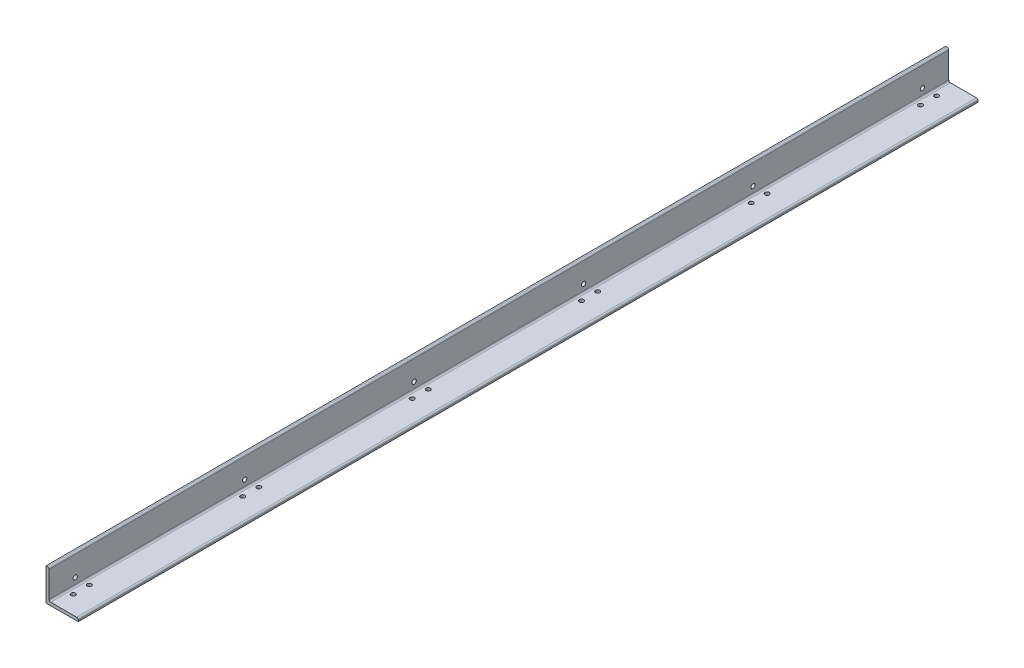
SolidWorks part; units mm, degrees
material "6061 Alloy"
ref_plane "Front Plane" through (0, 0, 0) normal (0, 0, 1) x (1, 0, 0)
ref_plane "Top Plane" through (0, 0, 0) normal (0, 1, 0) x (1, 0, 0)
ref_plane "Right Plane" through (0, 0, 0) normal (1, 0, 0) x (0, 0, -1)
sketch "Sketch1" plane through (0, 0, 0) normal (0, 0, 1) x (1, 0, 0)
  line L0 (0, 0) -> (0, 50.8)
  line L1 (0, 50.8) -> (4.7625, 50.8)
  line L2 (4.7625, 50.8) -> (4.7625, 4.7625)
  line L3 (4.7625, 4.7625) -> (50.8, 4.7625)
  line L4 (50.8, 4.7625) -> (50.8, 0)
  line L5 (50.8, 0) -> (0, 0)
  dimension "D1" = 50.8
  dimension "D2" = 50.8
  dimension "D3" = 4.7625
extrude "Boss-Extrude1" add sketch "Sketch1" along normal mid plane 1416.05
fillet "Fillet1" radius 2.54 3 edges at (50.8, 4.7625, 0) (4.7625, 4.7625, 0) (4.7625, 50.8, 0)
hole_wizard "1/4 Clearance Hole1" positions "Sketch9" profile "Sketch8" hole size "1/4" standard "ANSI Inch" end condition up to next
sketch "Sketch9" plane through (0, 4.7625, 0) normal (0, 1, 0) x (1, 0, 0)
  line L2 (48.26, -708.025) -> (7.3025, -708.025) construction
  line L3 (50.8, 708.025) -> (50.8, -708.025) construction
  point P1 (14.2875, -679.45)
  point P13 (14.2875, -654.05)
  dimension "D1" = 36.5125
  dimension "D2" = 28.575
  dimension "D3" = 25.4
sketch "Sketch8" plane through (14.2875, 4.7625, 679.45) normal (1, 0, 0) x (0, 0, 1)
  line L0 (0, 0) -> (0, 4.7625)
  line L1 (0, 4.7625) -> (3.3782, 4.7625)
  line L2 (3.3782, 4.7625) -> (3.3782, 0)
  line L5 (3.3782, 0) -> (0, 0)
  line L11 (0, -6.35) -> (0, 107.95) construction
  dimension "Thru Hole Dia." = 6.7564
  dimension "Thru Hole Depth" = 4.7625
pattern_linear "LPattern1" count 6 spacing 266.7 along (0, 0, -1) of "1/4 Clearance Hole1"
ref_plane "Plane1" through (0, 0, 0) normal (0.7071, -0.7071, 0) x (-0.7071, -0.7071, 0)
hole_wizard "1/4 Clearance Hole4" positions "Sketch17" profile "Sketch16" hole size "1/4" standard "ANSI Inch" end condition up to next
sketch "Sketch17" plane through (0, 0, 0) normal (-1, 0, 0) x (0, 0, 1)
  line L0 (-708.025, 16.6687) -> (-659.6641, 16.6687) construction
  line L1 (-708.025, 50.8) -> (-708.025, 0) construction
  line L2 (708.025, 0) -> (-708.025, 0) construction
  point P6 (-666.75, 16.6687)
  dimension "D1" = 41.275
  dimension "D2" = 16.6687
sketch "Sketch16" plane through (0, 16.6687, -666.75) normal (0, 1, 0) x (0, 0, 1)
  line L0 (0, 0) -> (0, 4.7625)
  line L1 (0, 4.7625) -> (3.3782, 4.7625)
  line L2 (3.3782, 4.7625) -> (3.3782, 0)
  line L5 (3.3782, 0) -> (0, 0)
  line L11 (0, -6.35) -> (0, 107.95) construction
  dimension "Thru Hole Dia." = 6.7564
  dimension "Thru Hole Depth" = 4.7625
pattern_linear "LPattern4" count 6 spacing 266.7 along (0, 0, 1) of "1/4 Clearance Hole4"
